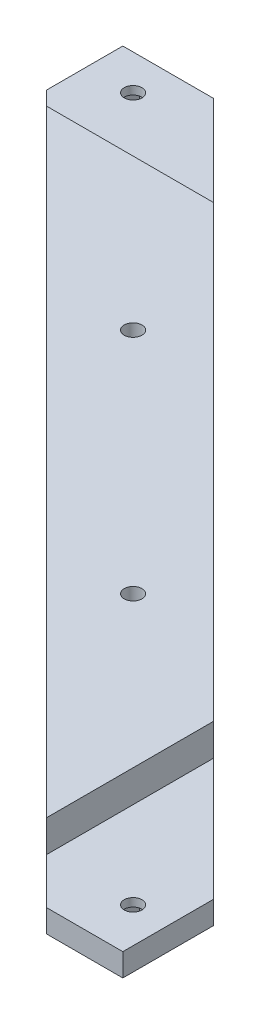
SolidWorks part; units mm, degrees
ref_plane "Front Plane" through (0, 0, 0) normal (0, 0, 1) x (1, 0, 0)
ref_plane "Top Plane" through (0, 0, 0) normal (0, 1, 0) x (1, 0, 0)
ref_plane "Right Plane" through (0, 0, 0) normal (1, 0, 0) x (0, 0, -1)
sketch "Sketch1" plane through (0, 0, 0) normal (0, 1, 0) x (1, 0, 0)
  line L0 (0, 0) -> (20, 0)
  line L1 (0, 0) -> (0, -17)
  line L2 (0, -17) -> (155, -172)
  line L3 (155, -172) -> (172, -172)
  line L4 (172, -172) -> (172, -152)
  line L5 (172, -152) -> (20, 0)
  dimension "D1" = 135
  dimension "D2" = 20
  dimension "D3" = 17
  dimension "D4" = 20
  dimension "D5" = 155
extrude "Boss-Extrude1" add sketch "Sketch1" along normal blind 12
sketch "Sketch2" plane through (0, 12, 0) normal (0, 1, 0) x (1, 0, 0)
  line L0 (0, 0) -> (0, -17) construction
  line L1 (20, 0) -> (0, 0) construction
  line L2 (172, -172) -> (172, -152) construction
  line L3 (155, -172) -> (172, -172) construction
  circle A0 centre (10, -8) radius 1.95
  circle A1 centre (164, -162) radius 1.95
  dimension "D3" = 3.9
  dimension "D6" = 3.9
  dimension "D1" = 10
  dimension "D2" = 8
  dimension "D4" = 8
  dimension "D5" = 10
extrude "Cut-Extrude1" cut sketch "Sketch2" against normal through all
sketch "Sketch3" plane through (0, 12, 0) normal (0, 1, 0) x (1, 0, 0)
  line L0 (172, -152) -> (20, 0) construction
  line L1 (0, 0) -> (47, 0)
  line L2 (0, 0) -> (0, -27)
  line L3 (0, -27) -> (47, -27)
  line L4 (47, 0) -> (47, -27)
  line L6 (172, -172) -> (145, -172)
  line L7 (172, -172) -> (172, -125)
  line L8 (172, -125) -> (145, -125)
  line L9 (145, -172) -> (145, -125)
  dimension "D1" = 27
  dimension "D2" = 27
extrude "Cut-Extrude2" cut sketch "Sketch3" against normal blind 7
sketch "Sketch5" plane through (0, 0, 0) normal (0, 1, 0) x (1, 0, 0)
  line L0 (10, -8) -> (164, -162) construction
  line L1 (20, 0) -> (0, 0) construction
  line L3 (172, -172) -> (172, -152) construction
  circle A0 centre (62, -60) radius 1.95
  circle A1 centre (112, -110) radius 1.95
  dimension "D3" = 3.9
  dimension "D4" = 3.9
  dimension "D1" = 60
  dimension "D2" = 60
extrude "Cut-Extrude8" cut sketch "Sketch5" along normal through all both and the other way through all
sketch "Sketch7" plane through (0, 0, 0) normal (0, -1, 0) x (1, 0, 0)
  line L1 (13.9837, 8) -> (11.9919, 11.45)
  line L2 (11.9919, 11.45) -> (8.0081, 11.45)
  line L3 (8.0081, 11.45) -> (6.0163, 8)
  line L4 (6.0163, 8) -> (8.0081, 4.55)
  line L5 (8.0081, 4.55) -> (11.9919, 4.55)
  line L6 (11.9919, 4.55) -> (13.9837, 8)
  line L7 (167.9837, 162) -> (165.9919, 165.45)
  line L8 (165.9919, 165.45) -> (162.0081, 165.45)
  line L9 (162.0081, 165.45) -> (160.0163, 162)
  line L10 (160.0163, 162) -> (162.0081, 158.55)
  line L11 (162.0081, 158.55) -> (165.9919, 158.55)
  line L12 (165.9919, 158.55) -> (167.9837, 162)
  line L13 (20, 0) -> (0, 0) construction
  line L14 (155, 172) -> (172, 172) construction
  circle A0 centre (10, 8) radius 3.45 construction
  circle A1 centre (164, 162) radius 3.45 construction
  dimension "D1" = 6.9
  dimension "D2" = 6.9
extrude "Cut-Extrude9" cut sketch "Sketch7" against normal blind 3.2
sketch "Sketch8" plane through (0, 0, 0) normal (0, -1, 0) x (1, 0, 0)
  line L6 (0, 0) -> (0, -10)
  line L7 (0, -10) -> (181.75, -10)
  line L8 (181.75, -10) -> (181.75, 172)
  line L9 (171.75, 172) -> (171.75, 152.1036)
  line L10 (171.75, 152.1036) -> (19.8964, 0.25)
  line L11 (19.8964, 0.25) -> (0, 0.25)
  line L12 (171.75, 172) -> (171.75, 152.1036)
  line L13 (171.75, 152.1036) -> (19.8964, 0.25)
  line L14 (19.8964, 0.25) -> (0, 0.25)
  line L15 (181.75, 172) -> (171.75, 172)
  dimension "D2" = 10
  dimension "D3" = 10
  dimension "D1" = 0.25
extrude "Cut-Extrude10" cut sketch "Sketch8" against normal through all and the other way through all
